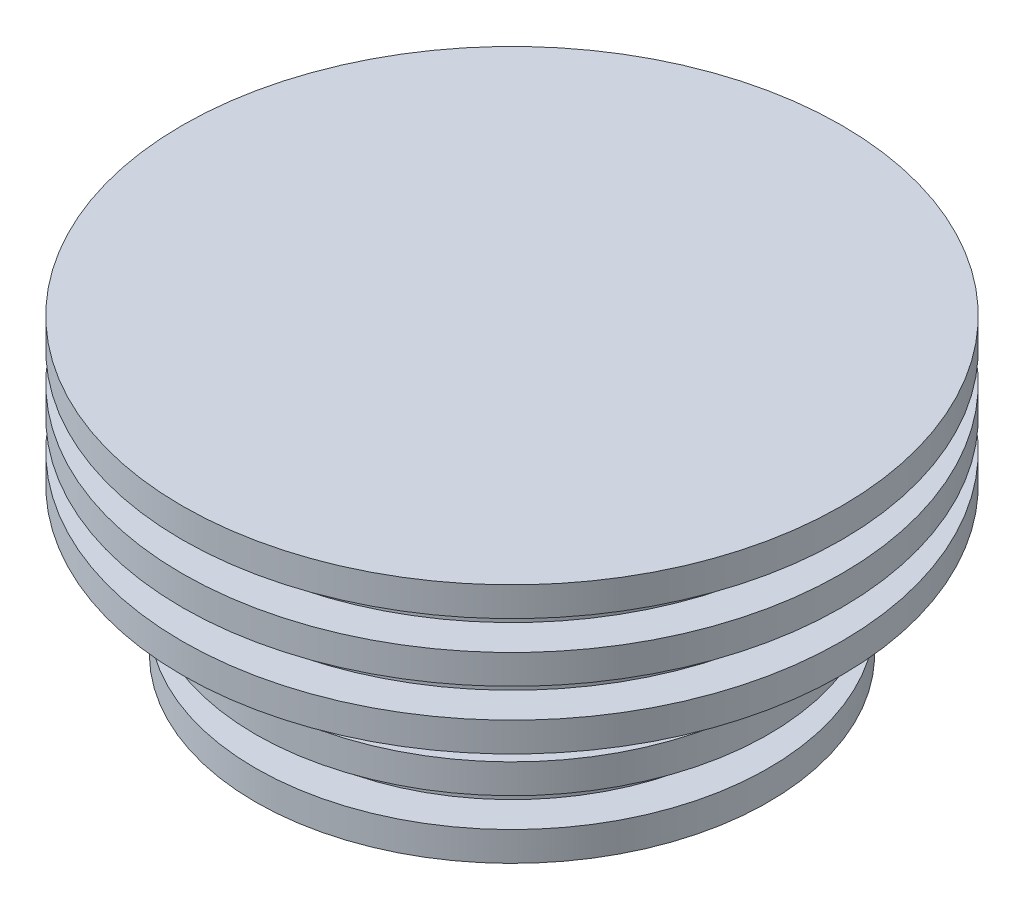
SolidWorks part; units mm, degrees
ref_plane "Front Plane" through (0, 0, 0) normal (0, 0, 1) x (1, 0, 0)
ref_plane "Top Plane" through (0, 0, 0) normal (0, 1, 0) x (1, 0, 0)
ref_plane "Right Plane" through (0, 0, 0) normal (1, 0, 0) x (0, 0, -1)
sketch "Sketch1" plane through (0, 0, 0) normal (0, 1, 0) x (1, 0, 0)
  circle A0 centre (0, 0) radius 22.225
  circle A1 centre (0, 0) radius 19.05
  dimension "D1" = 44.45
  dimension "D2" = 38.1
extrude "Boss-Extrude1" add sketch "Sketch1" along normal blind 2.54
sketch "Sketch3" plane through (0, 0, 0) normal (0, -1, 0) x (1, 0, 0)
  circle A0 centre (0, 0) radius 19.05
  dimension "D1" = 38.1
extrude "Boss-Extrude2" add sketch "Sketch3" against normal blind 12.7
pattern_linear "LPattern1" count 3 spacing 5.08 along (0, 1, 0) of "Boss-Extrude1"
sketch "Sketch5" plane through (0, 12.7, 0) normal (0, 1, 0) x (1, 0, 0)
  circle A0 centre (0, 0) radius 28.575
  circle A1 centre (0, 0) radius 25.4
  circle M1 centre (0, 0) radius 22.225
  dimension "D1" = 57.15
  dimension "D2" = 50.8
extrude "Boss-Extrude3" add sketch "Sketch5" along normal blind 12.7 contours A1 M1 | M1
sketch "Sketch7" plane through (0, 12.7, 0) normal (0, -1, 0) x (1, 0, 0)
  circle A0 centre (0, 0) radius 28.575
  dimension "D1" = 57.15
extrude "Boss-Extrude4" add sketch "Sketch7" against normal blind 2.54
pattern_linear "LPattern2" count 3 spacing 5.08 along (0, 1, 0) of "Boss-Extrude4"
